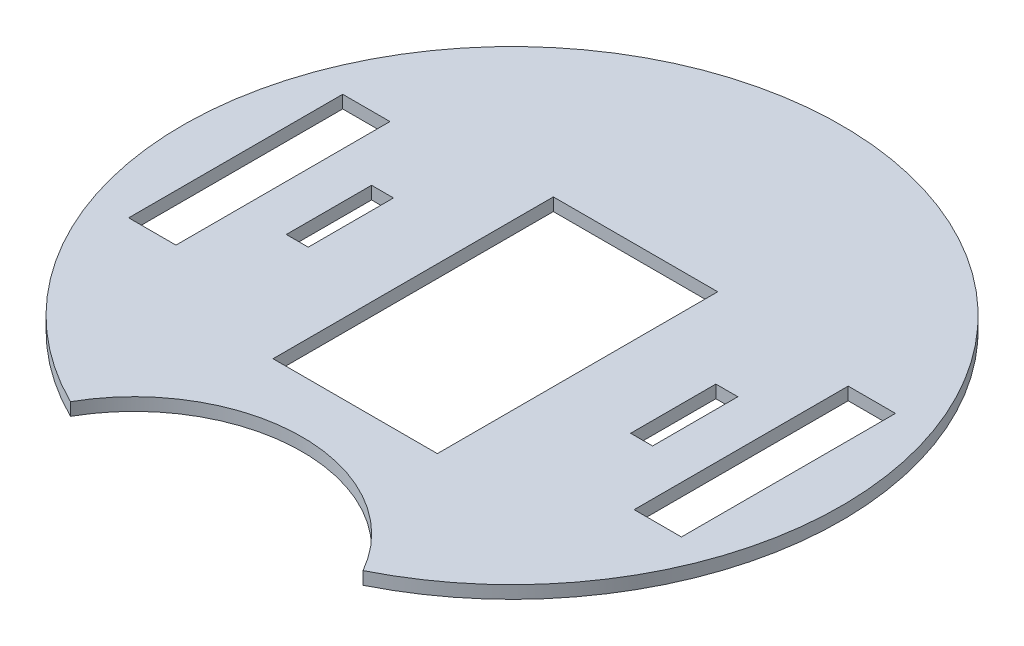
SolidWorks part; units mm, degrees
ref_plane "Front Plane" through (0, 0, 0) normal (0, 0, 1) x (1, 0, 0)
ref_plane "Top Plane" through (0, 0, 0) normal (0, 1, 0) x (1, 0, 0)
ref_plane "Right Plane" through (0, 0, 0) normal (1, 0, 0) x (0, 0, -1)
sketch "Sketch1" plane through (0, 0, 0) normal (0, 1, 0) x (1, 0, 0)
  line L0 (0, -86.0416) -> (-33.2911, -67.2064) construction
  line L1 (0, -86.0416) -> (0, 0) construction
  arc A0 (33.2911, -67.2064) -> (-33.2911, -67.2064) centre (0, 0) ccw
  arc A1 (33.2911, -67.2064) -> (-33.2911, -67.2064) centre (0, -86.0416) ccw
  dimension "D1" = 150
  dimension "D2" = 76.5
  dimension "D3" = 60.5
extrude "Boss-Extrude1" add sketch "Sketch1" along normal blind 2.9
sketch "solenoid placement" plane through (0, 2.9, 0) normal (0, 1, 0) x (1, 0, 0)
  line L0 (0, 0) -> (0, -36) construction
  line L1 (0, -36) -> (0, -47.7916) construction
  line L2 (-19, -36) -> (19, -36) construction
  line L3 (-19, -36) -> (-19, 28.4) construction
  line L4 (-19, 28.4) -> (19, 28.4) construction
  line L5 (19, -36) -> (19, 28.4) construction
  line L6 (-18.7, 28.1) -> (18.7, 28.1)
  line L7 (18.7, -35.7) -> (18.7, 28.1)
  line L8 (-18.7, -35.7) -> (18.7, -35.7)
  line L9 (-18.7, -35.7) -> (-18.7, 28.1)
  circle A1 centre (0, 0) radius 75 construction
  arc A2 (33.2911, -67.2064) -> (-33.2911, -67.2064) centre (0, 0) ccw construction
  arc A3 (33.2911, -67.2064) -> (-33.2911, -67.2064) centre (0, -86.0416) ccw construction
  dimension "D1" = 64.4
  dimension "D2" = 36
  dimension "D3" = 0.3
  dimension "D4" = 38
extrude "Cut-Extrude1" cut sketch "solenoid placement" against normal through all
sketch "Sketch2" plane through (0, 2.9, 0) normal (0, 1, 0) x (1, 0, 0)
  line L0 (52.4375, -24.0528) -> (52.4375, 24.0528) construction
  line L1 (-62.5975, -24.0528) -> (-52.4375, -24.0528) construction
  line L2 (-62.5975, -24.0528) -> (-62.5975, 24.0528) construction
  line L3 (-62.5975, 24.0528) -> (-52.4375, 24.0528) construction
  line L4 (-52.4375, -24.0528) -> (-52.4375, 24.0528) construction
  line L5 (62.5975, 24.0528) -> (52.4375, 24.0528) construction
  line L6 (62.5975, -24.0528) -> (62.5975, 24.0528) construction
  line L7 (62.5975, -24.0528) -> (52.4375, -24.0528) construction
  line L8 (62.8975, -24.3528) -> (62.8975, 24.3528)
  line L9 (62.8975, -24.3528) -> (52.1375, -24.3528)
  line L10 (52.1375, -24.3528) -> (52.1375, 24.3528)
  line L11 (62.8975, 24.3528) -> (52.1375, 24.3528)
  line L12 (0, 0) -> (0, 75) construction
  line L13 (-62.8975, 24.3528) -> (-52.1375, 24.3528)
  line L14 (-52.1375, -24.3528) -> (-52.1375, 24.3528)
  line L15 (-62.8975, -24.3528) -> (-52.1375, -24.3528)
  line L16 (-62.8975, -24.3528) -> (-62.8975, 24.3528)
  arc A0 (33.2911, -67.2064) -> (-33.2911, -67.2064) centre (0, 0) ccw construction
  point P17 (0, 0)
  point P24 (0, 0)
  point P26 (0, 0)
  point P27 (0, 0)
  point P28 (0, 0)
  point P29 (0, 0)
  point P33 (0, 0)
  dimension "D1" = 0.3
extrude "Cut-Extrude2" cut sketch "Sketch2" against normal through all
sketch "Sketch3" plane through (0, 2.9, 0) normal (0, 1, 0) x (1, 0, 0)
  line L4 (-41.6799, -9.7) -> (-36.6799, -9.7)
  line L5 (-36.6799, -9.7) -> (-36.6799, 9.7)
  line L6 (-36.6799, 9.7) -> (-41.6799, 9.7)
  line L7 (-41.6799, 9.7) -> (-41.6799, -9.7)
  line L8 (-41.6799, -9.7) -> (-36.6799, -9.7)
  line L9 (-36.6799, -9.7) -> (-36.6799, 9.7)
  line L10 (-36.6799, 9.7) -> (-41.6799, 9.7)
  line L11 (-41.6799, 9.7) -> (-41.6799, -9.7)
  line L12 (41.6799, -9.7) -> (41.6799, 9.7)
  line L13 (41.6799, 9.7) -> (36.6799, 9.7)
  line L14 (36.6799, 9.7) -> (36.6799, -9.7)
  line L15 (36.6799, -9.7) -> (41.6799, -9.7)
  line L16 (41.6799, -9.7) -> (41.6799, 9.7)
  line L17 (41.6799, 9.7) -> (36.6799, 9.7)
  line L18 (36.6799, 9.7) -> (36.6799, -9.7)
  line L19 (36.6799, -9.7) -> (41.6799, -9.7)
  dimension "D1" = 0
  dimension "D2" = 0
extrude "Cut-Extrude3" cut sketch "Sketch3" against normal through all
equation "\"smallPulleyTeeth\"= 15"
equation "\"largePulleyTeeth\"= 30"
equation "\"eighthThick\"= 2.9mm"
equation "\"sixteenthThick\" = 1.7mm"
equation "\"wheelEighthThick\"=3.0mm"
equation "\"quarterThick\"=5.6mm"
equation "\"OD\" = 150mm"
equation "\"puckAngle\" = 60.5deg"
equation "\"D1@Sketch1\"=\"OD\""
equation "\"puckDiam\" = 76.5mm"
equation "\"D2@Sketch1\"=\"puckDiam\""
equation "\"D3@Sketch1\"=\"puckAngle\""
equation "\"D1@Boss-Extrude1\"=\"eighthThick\""
equation "\"axlePress\" = 5.8mm"
equation "\"press\" = 0.3mm"
equation "\"wheelClear\" = 0.3mm"
equation "\"D1@Sketch2\"=\"wheelClear\""
